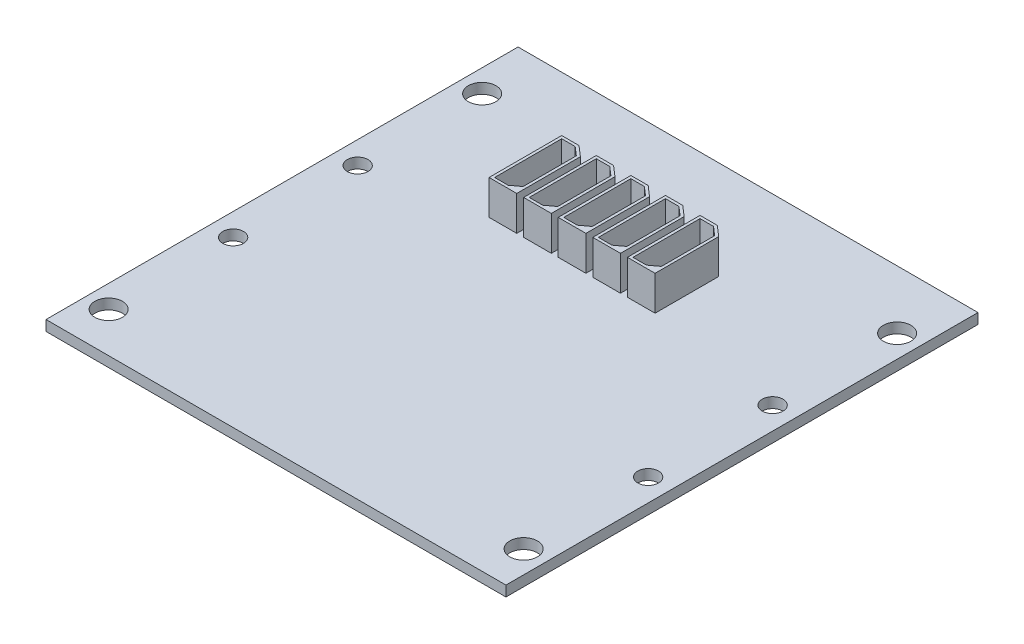
SolidWorks part; units mm, degrees
ref_plane "Front Plane" through (0, 0, 0) normal (0, 0, 1) x (1, 0, 0)
ref_plane "Top Plane" through (0, 0, 0) normal (0, 1, 0) x (1, 0, 0)
ref_plane "Right Plane" through (0, 0, 0) normal (1, 0, 0) x (0, 0, -1)
sketch "Sketch1" plane through (0, 0, 0) normal (0, 1, 0) x (1, 0, 0)
  line L1 (-33.25, 34.125) -> (33.25, 34.125)
  line L2 (-33.25, 34.125) -> (-33.25, -34.125)
  line L3 (-33.25, -34.125) -> (33.25, -34.125)
  line L4 (33.25, 34.125) -> (33.25, -34.125)
  line L5 (-33.25, 34.125) -> (33.25, -34.125) construction
  line L6 (-33.25, -34.125) -> (33.25, 34.125) construction
  point P0 (0, 0)
  dimension "D1" = 68.25
  dimension "D2" = 66.5
extrude "Boss-Extrude1" add sketch "Sketch1" along normal blind 1.5
sketch "Sketch3" plane through (0, 1.5, 0) normal (0, 1, 0) x (1, 0, 0)
  line L2 (0, 34.125) -> (0, -34.125) construction
  line L3 (33.25, 34.125) -> (-33.25, 34.125) construction
  line L4 (-33.25, -34.125) -> (33.25, -34.125) construction
  circle A0 centre (-30, -28.3176) radius 2
  circle A1 centre (30, -28.3176) radius 2
  circle A2 centre (30, 25.6824) radius 2
  circle A3 centre (-30, 25.6824) radius 2
  circle A4 centre (30, 7.6824) radius 1.5
  circle A5 centre (30, -10.3176) radius 1.5
  circle A6 centre (-30, -10.3176) radius 1.5
  circle A7 centre (-30, 7.6824) radius 1.5
  point P20 (0, 0)
  point P23 (0, 0)
  point P24 (0, 0)
  point P25 (0, 0)
  dimension "D7" = 4
  dimension "D8" = 4
  dimension "D9" = 4
  dimension "D10" = 4
  dimension "D14" = 3
  dimension "D15" = 3
  dimension "D1" = 60
  dimension "D2" = 30
  dimension "D3" = 30
  dimension "D4" = 54
  dimension "D5" = 54
  dimension "D6" = 30
  dimension "D11" = 18
  dimension "D12" = 18
  dimension "D13" = 18
extrude "Cut-Extrude1" cut sketch "Sketch3" against normal through all
sketch "Sketch5" plane through (0, 1.5, 0) normal (0, 1, 0) x (1, 0, 0)
  line L5 (-14.0063, 21.1916) -> (-11.5063, 21.1916)
  line L6 (-11.5063, 21.1916) -> (-10.0063, 19.8916)
  line L8 (-10.0063, 19.8916) -> (-10.0063, 10.6916)
  line L9 (-10.0063, 10.6916) -> (-14.0063, 10.6916)
  line L10 (-14.0063, 10.6916) -> (-14.0063, 21.1916)
  line L11 (-10.4063, 19.7089) -> (-10.4063, 12.0089)
  line L12 (-11.6563, 11.0916) -> (-13.6063, 11.0916)
  line L13 (-13.6063, 11.0916) -> (-13.6063, 20.7916)
  line L14 (-13.6063, 20.7916) -> (-11.6555, 20.7916)
  line L15 (-11.6555, 20.7916) -> (-10.4063, 19.7089)
  line L16 (-10.4063, 12.0089) -> (-11.6563, 11.0916)
  line L17 (-10.4063, 19.7089) -> (-10.4063, 11.0916) construction
  line L18 (-10.4063, 11.0916) -> (-13.6063, 11.0916) construction
  line L19 (-9.0063, 21.1916) -> (-6.5063, 21.1916)
  line L20 (-6.5063, 21.1916) -> (-5.0063, 19.8916)
  line L21 (-5.0063, 19.8916) -> (-5.0063, 10.6916)
  line L22 (-5.0063, 10.6916) -> (-9.0063, 10.6916)
  line L23 (-9.0063, 10.6916) -> (-9.0063, 21.1916)
  line L24 (-5.4063, 19.7089) -> (-5.4063, 12.0089)
  line L25 (-6.6563, 11.0916) -> (-8.6063, 11.0916)
  line L26 (-8.6063, 11.0916) -> (-8.6063, 20.7916)
  line L27 (-8.6063, 20.7916) -> (-6.6555, 20.7916)
  line L28 (-6.6555, 20.7916) -> (-5.4063, 19.7089)
  line L29 (-5.4063, 12.0089) -> (-6.6563, 11.0916)
  line L30 (-4.0063, 21.1916) -> (-1.5063, 21.1916)
  line L31 (-1.5063, 21.1916) -> (-0.0063, 19.8916)
  line L32 (-0.0063, 19.8916) -> (-0.0063, 10.6916)
  line L33 (-0.0063, 10.6916) -> (-4.0063, 10.6916)
  line L34 (-4.0063, 10.6916) -> (-4.0063, 21.1916)
  line L35 (-0.4063, 19.7089) -> (-0.4063, 12.0089)
  line L36 (-1.6563, 11.0916) -> (-3.6063, 11.0916)
  line L37 (-3.6063, 11.0916) -> (-3.6063, 20.7916)
  line L38 (-3.6063, 20.7916) -> (-1.6555, 20.7916)
  line L39 (-1.6555, 20.7916) -> (-0.4063, 19.7089)
  line L40 (-0.4063, 12.0089) -> (-1.6563, 11.0916)
  line L41 (0.9937, 21.1916) -> (3.4937, 21.1916)
  line L42 (3.4937, 21.1916) -> (4.9937, 19.8916)
  line L43 (4.9937, 19.8916) -> (4.9937, 10.6916)
  line L44 (4.9937, 10.6916) -> (0.9937, 10.6916)
  line L45 (0.9937, 10.6916) -> (0.9937, 21.1916)
  line L46 (4.5937, 19.7089) -> (4.5937, 12.0089)
  line L47 (3.3437, 11.0916) -> (1.3937, 11.0916)
  line L48 (1.3937, 11.0916) -> (1.3937, 20.7916)
  line L49 (1.3937, 20.7916) -> (3.3445, 20.7916)
  line L50 (3.3445, 20.7916) -> (4.5937, 19.7089)
  line L51 (4.5937, 12.0089) -> (3.3437, 11.0916)
  line L52 (5.9937, 21.1916) -> (8.4937, 21.1916)
  line L53 (8.4937, 21.1916) -> (9.9937, 19.8916)
  line L54 (9.9937, 19.8916) -> (9.9937, 10.6916)
  line L55 (9.9937, 10.6916) -> (5.9937, 10.6916)
  line L56 (5.9937, 10.6916) -> (5.9937, 21.1916)
  line L57 (9.5937, 19.7089) -> (9.5937, 12.0089)
  line L58 (8.3437, 11.0916) -> (6.3937, 11.0916)
  line L59 (6.3937, 11.0916) -> (6.3937, 20.7916)
  line L60 (6.3937, 20.7916) -> (8.3445, 20.7916)
  line L61 (8.3445, 20.7916) -> (9.5937, 19.7089)
  line L62 (9.5937, 12.0089) -> (8.3437, 11.0916)
  line L63 (-14.0063, 21.1916) -> (-9.0063, 21.1916) construction
  dimension "D1" = 7.7
  dimension "D2" = 10.5
  dimension "D3" = 4
  dimension "D4" = 2.5
  dimension "D6" = 1.95
  dimension "D8" = 5
  dimension "D5" = 0.4
  dimension "D7" = 5
extrude "Boss-Extrude2" add sketch "Sketch5" along normal blind 5
